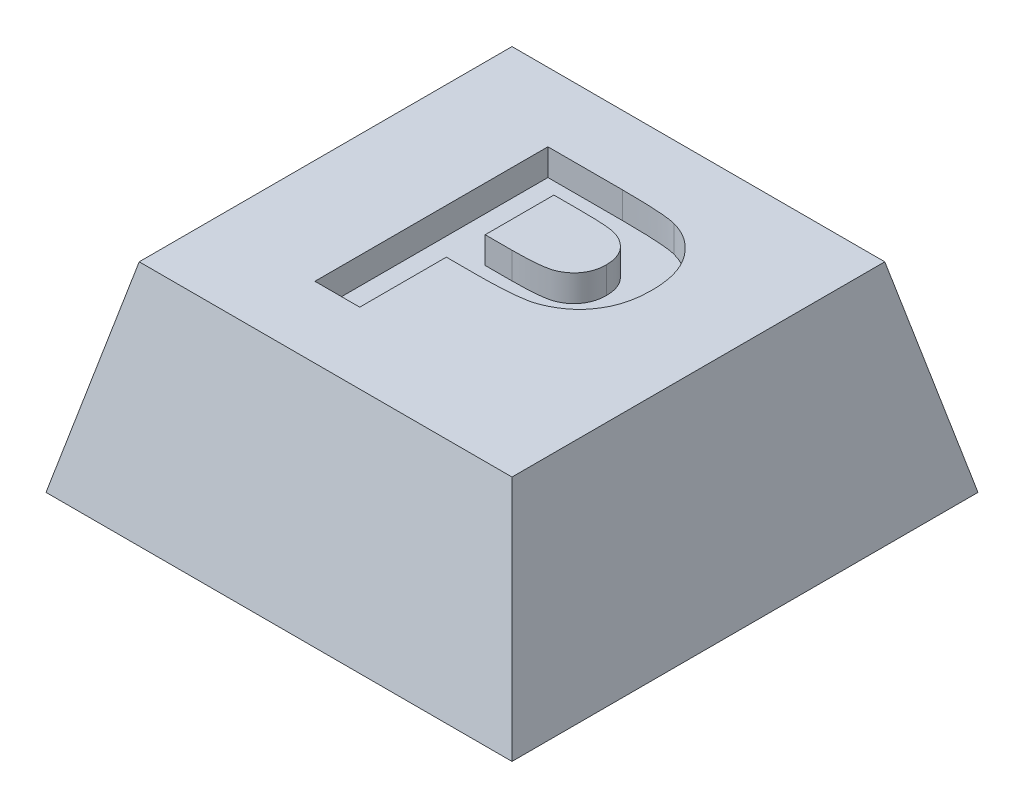
SolidWorks part; units mm, degrees
ref_plane "Front Plane" through (0, 0, 0) normal (0, 0, 1) x (1, 0, 0)
ref_plane "Top Plane" through (0, 0, 0) normal (0, 1, 0) x (1, 0, 0)
ref_plane "Right Plane" through (0, 0, 0) normal (1, 0, 0) x (0, 0, -1)
sketch "Sketch1" plane through (0, 0, 0) normal (0, 1, 0) x (1, 0, 0)
  line L1 (0, 0) -> (7, 0)
  line L2 (0, 0) -> (0, 7)
  line L3 (0, 7) -> (7, 7)
  line L4 (7, 0) -> (7, 7)
  dimension "D1" = 7
  dimension "D2" = 7
extrude "Boss-Extrude1" add sketch "Sketch1" along normal blind 3
sketch "Sketch2" plane through (0, 0, 0) normal (0, 0, 1) x (1, 0, 0)
  line L0 (0, 0) -> (0.7, 3)
  line L1 (0, 3) -> (7, 3) construction
  line L2 (0.7, 3) -> (0, 3)
  line L3 (0, 3) -> (0, 0)
  line L4 (7, 0) -> (6.3, 3)
  line L5 (6.3, 3) -> (7, 3)
  line L6 (7, 3) -> (7, 0)
  dimension "D1" = 0.7
  dimension "D2" = 0.7
extrude "Cut-Extrude1" cut sketch "Sketch2" against normal blind 7
sketch "Sketch3" plane through (0, 0, 0) normal (1, 0, 0) x (0, 0, -1)
  line L0 (0, 0) -> (0.7, 3)
  line L1 (7, 3) -> (0, 3) construction
  line L2 (0.7, 3) -> (0, 3)
  line L3 (0, 3) -> (0, 0)
  line L4 (7, 3) -> (6.3, 3)
  line L5 (6.3, 3) -> (7, 0)
  line L6 (7, 3) -> (7, 0)
  dimension "D1" = 0.7
  dimension "D2" = 0.7
extrude "Cut-Extrude2" cut sketch "Sketch3" along normal blind 11
sketch "Sketch4" plane through (0, 0, 0) normal (0, -1, 0) x (1, 0, 0)
  line L0 (3.5, 0) -> (3.5, -7) construction
  line L1 (0, 0) -> (7, 0) construction
  line L2 (7, -7) -> (0, -7) construction
  line L3 (0, -3.5) -> (7, -3.5) construction
  line L4 (0, -7) -> (0, 0) construction
  line L5 (7, 0) -> (7, -7) construction
  circle A0 centre (3.5, -3.5) radius 1.8
  dimension "D1" = 3.6
extrude "Cut-Extrude3" cut sketch "Sketch4" against normal blind 0.8
sketch "Sketch5" plane through (0, 3, 0) normal (0, 1, 0) x (1, 0, 0)
  text T0 "P" font "Arial" height 3.5
extrude "Cut-Extrude4" cut sketch "Sketch5" against normal blind 0.4
